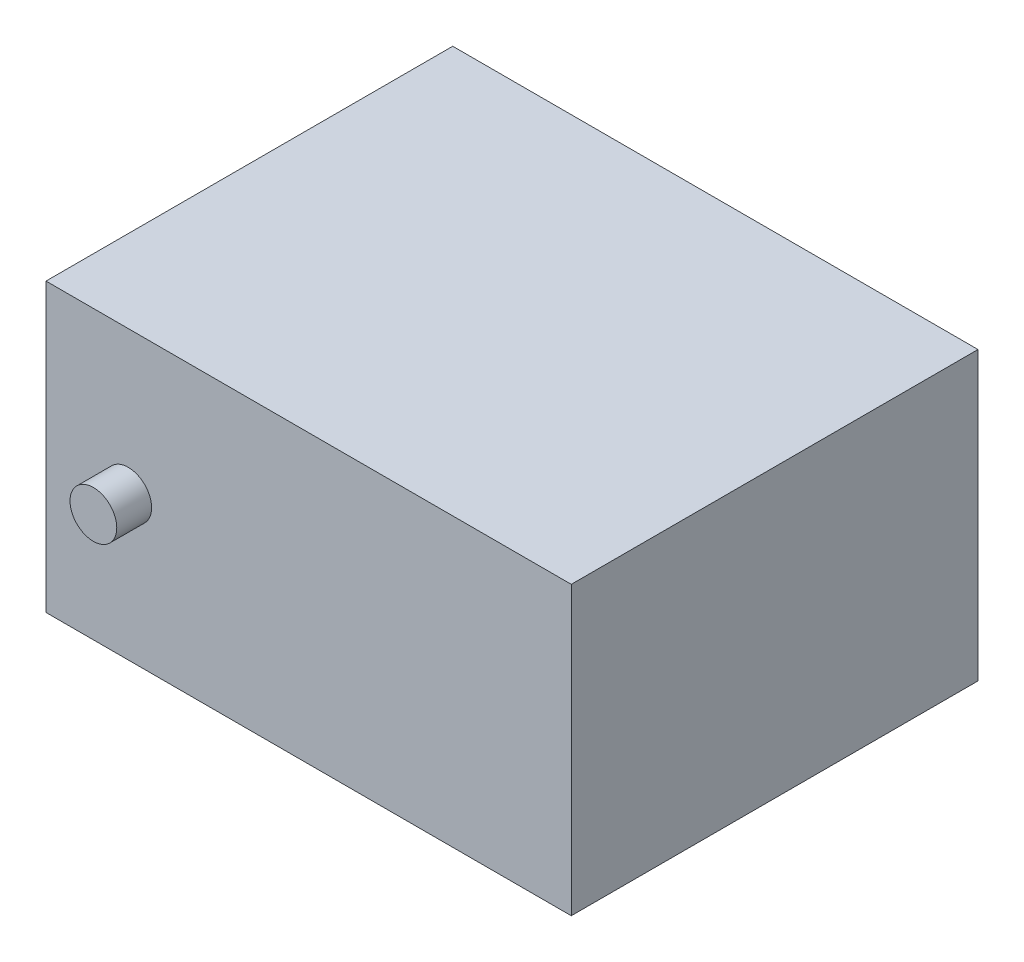
SolidWorks part; units mm, degrees
ref_plane "Front Plane" through (0, 0, 0) normal (0, 0, 1) x (1, 0, 0)
ref_plane "Top Plane" through (0, 0, 0) normal (0, 1, 0) x (1, 0, 0)
ref_plane "Right Plane" through (0, 0, 0) normal (1, 0, 0) x (0, 0, -1)
sketch "Sketch1" plane through (0, 0, 0) normal (0, 0, 1) x (1, 0, 0)
  line L1 (-22.6, -12.35) -> (22.6, -12.35)
  line L2 (-22.6, -12.35) -> (-22.6, 12.35)
  line L3 (-22.6, 12.35) -> (22.6, 12.35)
  line L4 (22.6, -12.35) -> (22.6, 12.35)
  line L5 (-22.6, -12.35) -> (22.6, 12.35) construction
  line L6 (-22.6, 12.35) -> (22.6, -12.35) construction
  point P0 (0, 0)
  dimension "D1" = 45.2
  dimension "D2" = 24.7
extrude "Boss-Extrude1" add sketch "Sketch1" along normal blind 35
sketch "Sketch2" plane through (0, 0, 35) normal (0, 0, 1) x (1, 0, 0)
  circle A0 centre (-15.5215, 0) radius 2.0103
extrude "Boss-Extrude2" add sketch "Sketch2" along normal blind 3
